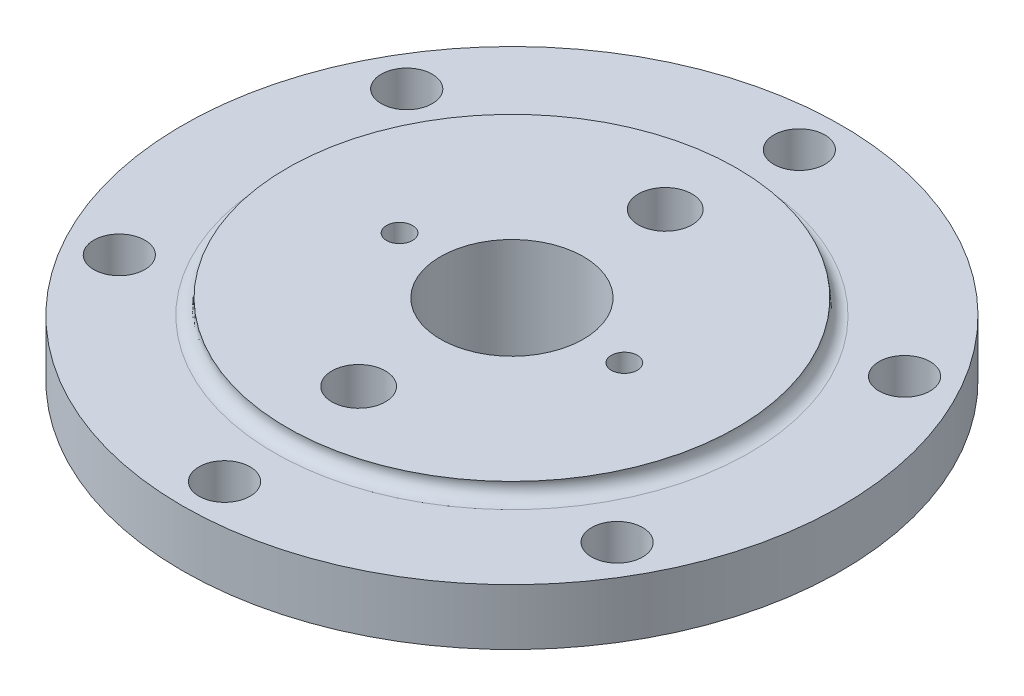
SolidWorks part; units mm, degrees
ref_plane "Front Plane" through (0, 0, 0) normal (0, 0, 1) x (1, 0, 0)
ref_plane "Top Plane" through (0, 0, 0) normal (0, 1, 0) x (1, 0, 0)
ref_plane "Right Plane" through (0, 0, 0) normal (1, 0, 0) x (0, 0, -1)
sketch "Sketch1" plane through (0, 0, 0) normal (1, 0, 0) x (0, 0, -1)
  line L0 (0, 0) -> (61.2687, 0) construction
  line L1 (61.2687, 0) -> (-50.747, 0) construction
  line L2 (0, 0) -> (0, 36.9878) construction
  line L3 (0, 0) -> (0, -30.9166) construction
  line L4 (14, 0) -> (35, 0)
  line L5 (35, 0) -> (81, 47)
  line L6 (81, 47) -> (81, 53)
  line L7 (81, 53) -> (138, 53)
  line L8 (138, 53) -> (138, 75)
  line L9 (138, 75) -> (93.0284, 75)
  line L10 (88, 81) -> (28, 81)
  line L11 (28, 81) -> (28, 35.0829)
  line L12 (28, 35.0829) -> (14, 27)
  line L13 (14, 27) -> (14, 0)
  arc A0 (93.0284, 75) -> (88, 81) centre (93.0284, 80.107) cw
  point P2 (138, 64)
  dimension "D1" = 14
  dimension "D2" = 28
  dimension "D3" = 88
  dimension "D4" = 138
  dimension "D5" = 81
  dimension "D6" = 35
  dimension "D7" = 6
  dimension "D8" = 22
  dimension "D9" = 6
  dimension "D10" = 47
  dimension "D11" = 60
  dimension "D12" = 48
revolve "Revolve1" add sketch "Sketch1" angle 360 about L2
sketch "Sketch2" plane through (0, 75, 0) normal (0, 1, 0) x (1, 0, 0)
  line L0 (0, 0) -> (0, 163.7328) construction
  circle A0 centre (0, 112.5) radius 10
  circle A1 centre (97.4279, 56.25) radius 10
  circle A2 centre (97.4279, -56.25) radius 10
  circle A3 centre (0, -112.5) radius 10
  circle A4 centre (-97.4279, -56.25) radius 10
  circle A5 centre (-97.4279, 56.25) radius 10
  point P18 (0, 0)
  dimension "D1" = 20
  dimension "D2" = 112.5
  dimension "D3" = 6
extrude "Cut-Extrude1" cut sketch "Sketch2" against normal through all
hole_wizard "M24 Tapped Hole1" positions "Sketch3" profile "Sketch4" tap size "M24" standard "ISO"
sketch "Sketch3" plane through (0, 81, 0) normal (0, 1, 0) x (1, 0, 0)
  line L0 (0, 60) -> (0, -60)
  point P1 (0, 60)
  point P2 (0, -60)
  point P13 (0, 0)
  dimension "D1" = 120
sketch "Sketch4" plane through (0, 81, -60) normal (1, 0, 0) x (0, 0, 1)
  line L0 (0, 0) -> (0, 33.309)
  line L1 (0, 33.309) -> (10.5, 27)
  line L2 (10.5, 27) -> (10.5, 0)
  line L5 (10.5, 0) -> (0, 0)
  line L10 (0, 33.309) -> (-10.5, 27) construction
  line L11 (0, -6.35) -> (0, 107.95) construction
  dimension "Tap Drill Dia." = 21
  dimension "Tap Drill Depth" = 27
  dimension "Drill Angle" = 118
cosmetic thread "Hole Thread1" parameters "D1"=24, "D2"=24
cosmetic thread "Hole Thread2" parameters "D1"=24, "D2"=24
hole_wizard "M12 Tapped Hole1" positions "Sketch5" profile "Sketch6" tap size "M12" standard "ISO"
sketch "Sketch5" plane through (0, 81, 0) normal (0, 1, 0) x (1, 0, 0)
  line L0 (-44, 0) -> (44, 0)
  point P1 (-44, 0)
  point P2 (44, 0)
  point P5 (0, 0)
  dimension "D1" = 88
sketch "Sketch6" plane through (-44, 81, 0) normal (1, 0, 0) x (0, 0, 1)
  line L0 (0, 0) -> (0, 18.0644)
  line L1 (0, 18.0644) -> (5.1, 15)
  line L2 (5.1, 15) -> (5.1, 0)
  line L5 (5.1, 0) -> (0, 0)
  line L10 (0, 18.0644) -> (-5.1, 15) construction
  line L11 (0, -6.35) -> (0, 107.95) construction
  dimension "Tap Drill Dia." = 10.2
  dimension "Tap Drill Depth" = 15
  dimension "Drill Angle" = 118
cosmetic thread "Hole Thread3" parameters "D1"=12, "D2"=12
cosmetic thread "Hole Thread4" parameters "D1"=12, "D2"=12
sketch "Sketch7" plane through (0, 81, 0) normal (0, 1, 0) x (1, 0, 0)
  circle A0 centre (0, 0) radius 129
  circle A1 centre (0, 0) radius 138 construction
  circle A2 centre (0, 0) radius 138
  dimension "D1" = 258
extrude "Cut-Extrude2" cut sketch "Sketch7" against normal blind 61
